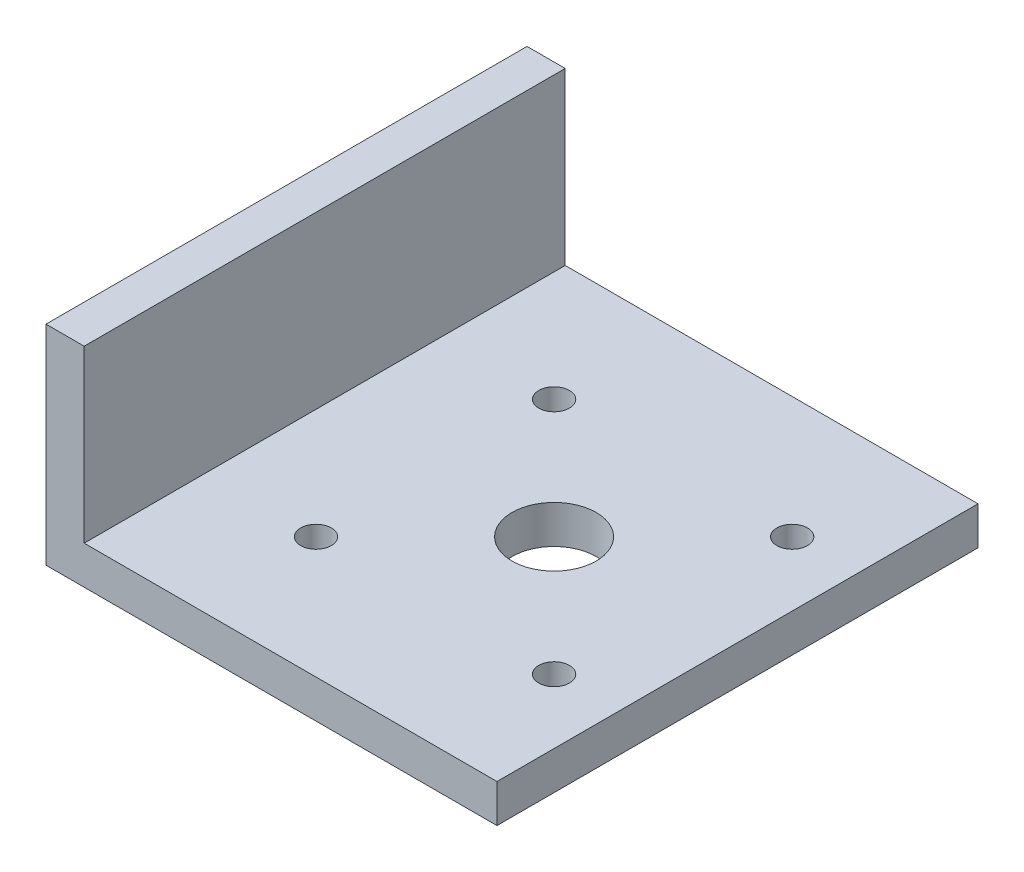
SolidWorks part; units mm, degrees
ref_plane "Front Plane" through (0, 0, 0) normal (0, 0, 1) x (1, 0, 0)
ref_plane "Top Plane" through (0, 0, 0) normal (0, 1, 0) x (1, 0, 0)
ref_plane "Right Plane" through (0, 0, 0) normal (1, 0, 0) x (0, 0, -1)
sketch "Sketch1" plane through (0, 0, 0) normal (0, 0, 1) x (1, 0, 0)
  line L0 (0, -37.5) -> (0, 37.5)
  line L1 (0, 37.5) -> (75, 37.5)
  line L2 (75, 37.5) -> (75, 31.15)
  line L3 (75, 31.15) -> (6.35, 31.15)
  line L4 (6.35, 31.15) -> (6.35, -31.15)
  line L5 (6.35, -31.15) -> (75, -31.15)
  line L6 (75, -31.15) -> (75, -37.5)
  line L7 (75, -37.5) -> (0, -37.5)
  line L8 (0, 0) -> (6.35, 0) construction
  dimension "D1" = 75
  dimension "D2" = 75
  dimension "D3" = 6.35
extrude "Boss-Extrude1" add sketch "Sketch1" along normal blind 80
sketch "Sketch2" plane through (0, 37.5, 0) normal (0, 1, 0) x (1, 0, 0)
  line L0 (40, -40) -> (0, -40) construction
  line L1 (0, -80) -> (0, 0) construction
  line L6 (75, 0) -> (6.35, 0)
  line L7 (75, -80) -> (75, 0)
  line L8 (6.35, -80) -> (75, -80)
  line L9 (6.35, 0) -> (6.35, -80)
  line L10 (75, 0) -> (6.35, 0)
  line L11 (75, -80) -> (75, 0)
  line L12 (6.35, -80) -> (75, -80)
  line L13 (6.35, 0) -> (6.35, -80)
  dimension "D2" = 0
  dimension "D1" = 40
extrude "Cut-Extrude1" cut sketch "Sketch2" against normal blind 10
sketch "Sketch3" plane through (0, -37.5, 0) normal (0, -1, 0) x (1, 0, 0)
  line L0 (75, 40) -> (6.8625, 40) construction
  line L1 (75, 80) -> (75, 0) construction
  circle A0 centre (44.5, 40) radius 7
  dimension "D1" = 14
  dimension "D2" = 30.5
extrude "Cut-Extrude2" cut sketch "Sketch3" against normal blind 10
sketch "Sketch4" plane through (0, -31.15, 0) normal (0, 1, 0) x (1, 0, 0)
  line L0 (64.299, -59.799) -> (64.299, -20.201) construction
  line L1 (64.299, -20.201) -> (24.701, -20.201) construction
  circle A0 centre (64.299, -20.201) radius 2.55
  circle A1 centre (64.299, -59.799) radius 2.55
  circle A2 centre (24.701, -59.799) radius 2.55
  circle A3 centre (24.701, -20.201) radius 2.55
  circle A4 centre (44.5, -40) radius 28 construction
  circle A5 centre (44.5, -40) radius 7 construction
  dimension "D1" = 5.1
  dimension "D2" = 56
extrude "Cut-Extrude3" cut sketch "Sketch4" against normal blind 10
sketch "Sketch5" plane through (6.35, 0, 0) normal (1, 0, 0) x (0, 0, -1)
  line L0 (110.0591, 58.6923) -> (-168.5596, 58.6923)
  line L1 (110.0591, 58.6923) -> (110.0591, -2.7755)
  line L2 (-168.5596, 58.6923) -> (-168.5596, -2.7755)
  line L3 (110.0591, -2.7755) -> (-168.5596, -2.7755)
  line L4 (110.0591, 58.6923) -> (-168.5596, -2.7755) construction
  line L5 (-168.5596, 58.6923) -> (110.0591, -2.7755) construction
  point P1 (-29.2502, 27.9584)
extrude "Cut-Extrude4" cut sketch "Sketch5" against normal blind 10
